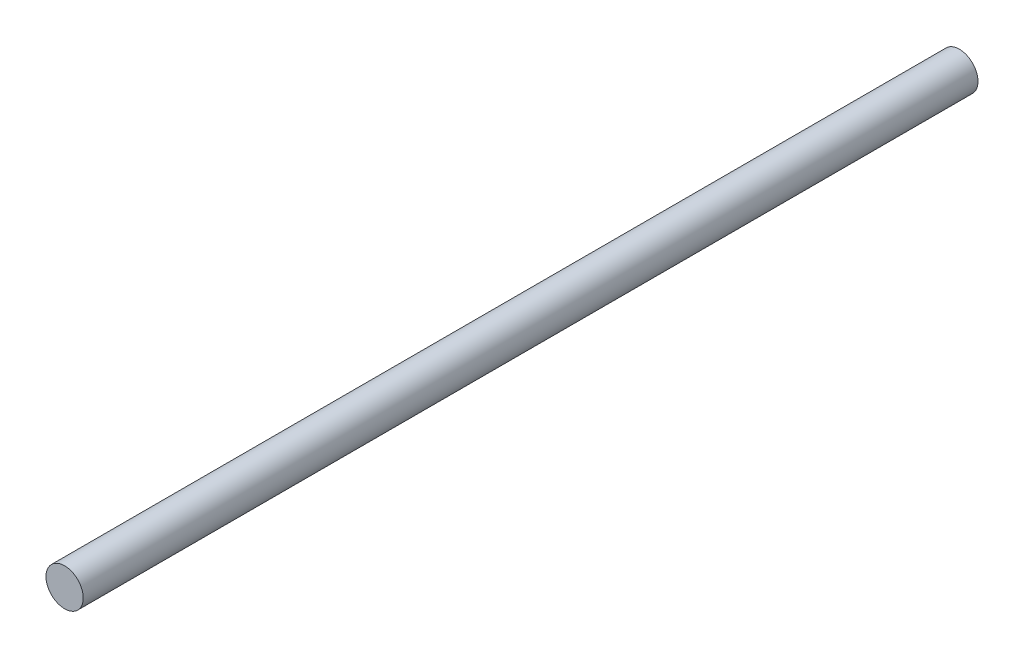
SolidWorks part; units mm, degrees
ref_plane "Спереди" through (0, 0, 0) normal (0, 0, 1) x (1, 0, 0)
ref_plane "Сверху" through (0, 0, 0) normal (0, 1, 0) x (1, 0, 0)
ref_plane "Справа" through (0, 0, 0) normal (1, 0, 0) x (0, 0, -1)
sketch "Эскиз1" plane through (0, 0, 0) normal (0, 0, 1) x (1, 0, 0)
  circle A0 centre (0, 0) radius 2
extrude "Tie_stud" add sketch "Эскиз1" along normal blind 96 from offset 38
